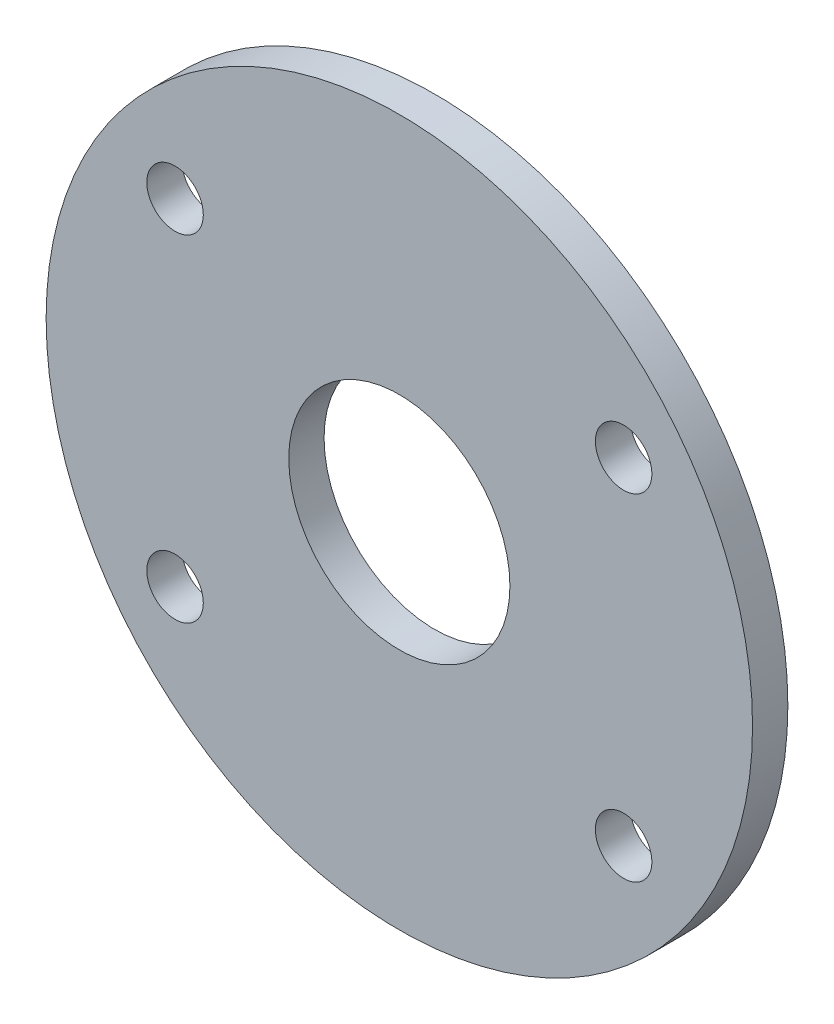
SolidWorks part; units mm, degrees
ref_plane "Front Plane" through (0, 0, 0) normal (0, 0, 1) x (1, 0, 0)
ref_plane "Top Plane" through (0, 0, 0) normal (0, 1, 0) x (1, 0, 0)
ref_plane "Right Plane" through (0, 0, 0) normal (1, 0, 0) x (0, 0, -1)
sketch "Sketch1" plane through (0, 0, 0) normal (0, 0, 1) x (1, 0, 0)
  line L0 (0, 50) -> (0, -50) construction
  line L1 (-50, 0) -> (50, 0) construction
  circle A0 centre (0, 0) radius 50
  circle A2 centre (-31.75, 23.7917) radius 4
  circle A3 centre (31.75, 23.7917) radius 4
  circle A4 centre (-31.75, -23.7917) radius 4
  circle A5 centre (31.75, -23.7917) radius 4
  circle A8 centre (0, 0) radius 39.675 construction
  point P3 (0, 0)
  point P16 (0, 0)
  point P17 (0, 0)
  point P19 (41.44, 29.5531)
  dimension "D1" = 100
  dimension "D2" = 79.35
  dimension "D3" = 63.5
  dimension "D4" = 8
  dimension "D6" = 8
  dimension "D7" = 8
  dimension "D8" = 8
  dimension "D5" = 63.5
extrude "Boss-Extrude1" add sketch "Sketch1" along normal blind 5
sketch "Sketch2" plane through (0, 0, 0) normal (0, 0, -1) x (-1, 0, 0)
  circle A0 centre (0, 0) radius 15.655
  dimension "D1" = 31.31
extrude "Cut-Extrude1" cut sketch "Sketch2" against normal blind 10
